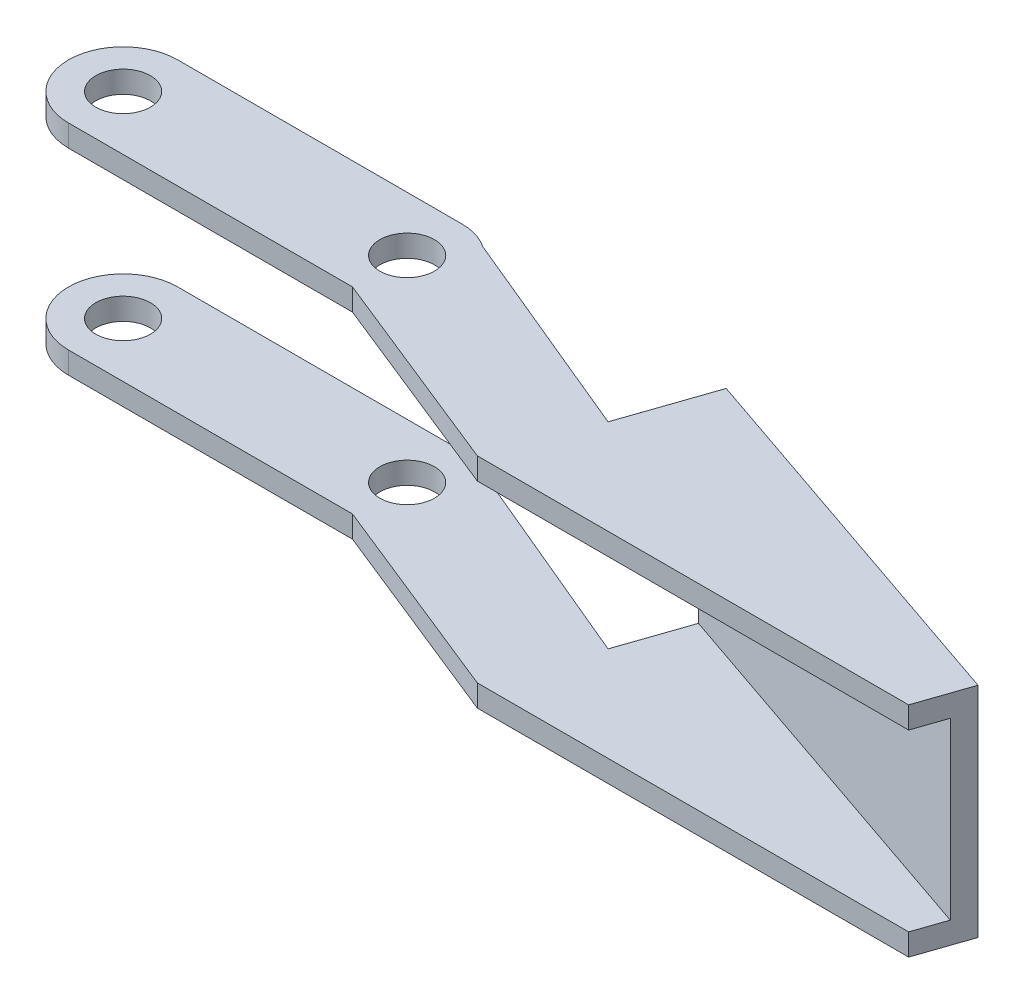
SolidWorks part; units mm, degrees
ref_plane "Front Plane" through (0, 0, 0) normal (0, 0, 1) x (1, 0, 0)
ref_plane "Top Plane" through (0, 0, 0) normal (0, 1, 0) x (1, 0, 0)
ref_plane "Right Plane" through (0, 0, 0) normal (1, 0, 0) x (0, 0, -1)
sketch "Sketch1" plane through (0, 0, 0) normal (0, 1, 0) x (1, 0, 0)
  line L0 (0, 0) -> (26, 0) construction
  line L1 (0, 5) -> (26, 5)
  line L2 (0, -5) -> (26, -5)
  arc A0 (0, 5) -> (0, -5) centre (0, 0) ccw
  arc A1 (26, -5) -> (26, 5) centre (26, 0) ccw
  circle A2 centre (0, 0) radius 2.5
  circle A3 centre (26, 0) radius 2.5
  point P3 (13, 0)
  dimension "D3" = 5
  dimension "D4" = 5
  dimension "D1" = 26
  dimension "D2" = 10
extrude "Boss-Extrude1" add sketch "Sketch1" along normal blind 2
sketch "Sketch2" plane through (0, 2, 0) normal (0, 1, 0) x (1, 0, 0)
  line L0 (26, 5) -> (63.1764, -9.942) construction
  line L1 (26, -5) -> (59.9415, -18.6419) construction
  line L2 (9.344, 5) -> (69.6955, 5) construction
  line L3 (26, 5) -> (0, 5) construction
  line L4 (9.344, -5) -> (50.8804, -5) construction
  line L5 (0, -5) -> (26, -5) construction
  line L6 (48.3923, 5) -> (48.3923, -5) construction
  line L7 (48.3923, 5) -> (111.444, -16.5904) construction
sketch "Sketch3" plane through (0, 2, 0) normal (0, 1, 0) x (1, 0, 0)
  line L0 (28.7977, 4.144) -> (48.3923, -4)
  line L1 (48.3923, 5) -> (48.3923, -5) construction
  line L2 (26, 5) -> (63.1764, -9.942) construction
  line L3 (28.7977, 4.144) -> (30.046, -0.3188)
  line L4 (51.1507, 4.0555) -> (86.2041, -7.9476)
  line L5 (48.3923, 5) -> (111.444, -16.5904) construction
  line L6 (30.046, -0.3188) -> (26, -5)
  line L7 (84.5843, -12.678) -> (45.1031, -12.678)
  line L8 (26, -5) -> (59.9415, -18.6419) construction
  line L9 (45.1031, -12.678) -> (26, -5)
  line L10 (9.344, 5) -> (69.6955, 5) construction
  line L11 (48.3923, -4) -> (51.1507, 4.0555)
  line L12 (86.2041, -7.9476) -> (84.5843, -12.678)
  arc A0 (26, -5) -> (26, 5) centre (26, 0) ccw construction
  dimension "D1" = 5
extrude "Boss-Extrude2" add sketch "Sketch3" against normal blind 2
sketch "Sketch4" plane through (0, 0, 0) normal (0, -1, 0) x (1, 0, 0)
  line L0 (51.1507, -4.0555) -> (86.2041, 7.9476)
  line L1 (51.1507, -4.0555) -> (50.5028, -2.1633)
  line L2 (86.2041, 7.9476) -> (85.5561, 9.8398)
  line L3 (50.5028, -2.1633) -> (85.5561, 9.8398)
  dimension "D1" = 2
extrude "Boss-Extrude3" add sketch "Sketch4" along normal blind 16
sketch "Sketch5" plane through (0, -16, 0) normal (0, -1, 0) x (1, 0, 0)
  line L0 (51.1507, -4.0555) -> (48.3923, 4)
  line L1 (48.3923, 4) -> (27.4629, -4.7812)
  line L2 (0, 0) -> (26, 0) construction
  line L3 (0, 5) -> (26, 5)
  line L4 (0, -5) -> (26, -5)
  line L5 (51.1507, -4.0555) -> (86.2041, 7.9476)
  line L6 (86.2041, 7.9476) -> (84.5843, 12.678)
  line L7 (84.5843, 12.678) -> (45.1031, 12.678)
  line L8 (45.1031, 12.678) -> (26, 5)
  arc A0 (26, -5) -> (28.7977, -4.144) centre (26, 0) ccw construction
  arc A1 (0, 5) -> (0, -5) centre (0, 0) ccw
  arc A2 (26, -5) -> (28.3866, -4.3937) centre (26, 0) ccw
  circle A3 centre (0, 0) radius 2.5
  circle A4 centre (26, 0) radius 2.5
  point P12 (13, 0)
  dimension "D1" = 10
extrude "Boss-Extrude4" add sketch "Sketch5" along normal blind 2
